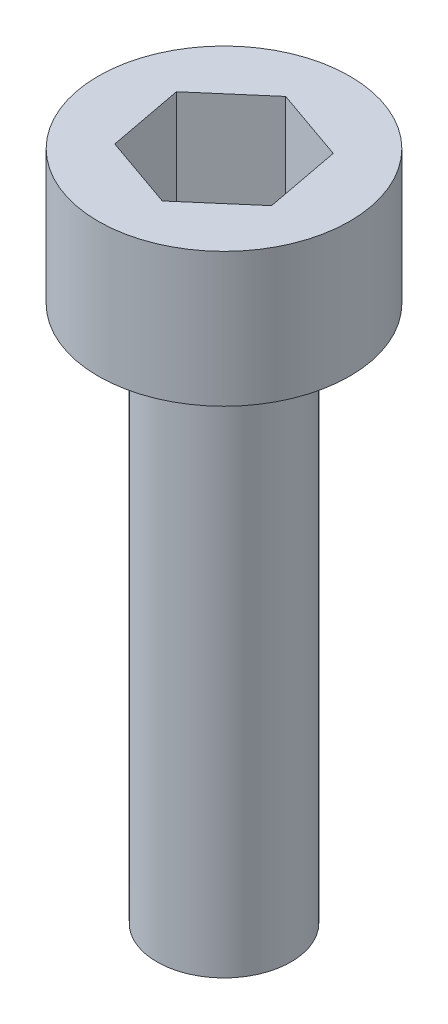
SolidWorks part; units mm, degrees
material "AISI 316L Acero inoxidable"
ref_plane "Alzado" through (0, 0, 0) normal (0, 0, 1) x (1, 0, 0)
ref_plane "Planta" through (0, 0, 0) normal (0, 1, 0) x (1, 0, 0)
ref_plane "Vista lateral" through (0, 0, 0) normal (1, 0, 0) x (0, 0, -1)
sketch "Croquis1" plane through (0, 0, 0) normal (0, 0, 1) x (1, 0, 0)
  line L0 (0, 0) -> (-1, 0)
  line L1 (-1, 0) -> (-1, 8)
  line L2 (-1, 8) -> (-1.875, 8)
  line L3 (-1.875, 8) -> (-1.875, 10)
  line L4 (-1.875, 10) -> (-0.5156, 10)
  line L5 (-0.5156, 10) -> (-0.5156, 8.3222)
  line L6 (-0.5156, 8.3222) -> (0, 8.3222)
  line L7 (0, 8.3222) -> (0, 0)
  dimension "D1" = 1
  dimension "D2" = 8
  dimension "D3" = 1.875
  dimension "D4" = 2
revolve "Revolución1" add sketch "Croquis1" angle 360 about L7
sketch "Croquis2" plane through (0, 10, 0) normal (0, 1, 0) x (1, 0, 0)
  line L1 (0.875, 0.7534) -> (-0.215, 1.1345)
  line L2 (-0.215, 1.1345) -> (-1.09, 0.3811)
  line L3 (-1.09, 0.3811) -> (-0.875, -0.7534)
  line L4 (-0.875, -0.7534) -> (0.215, -1.1345)
  line L5 (0.215, -1.1345) -> (1.09, -0.3811)
  line L6 (1.09, -0.3811) -> (0.875, 0.7534)
  circle A0 centre (0, 0) radius 1 construction
  dimension "D1" = 2
extrude "Cortar-Extruir1" cut sketch "Croquis2" against normal blind 2
